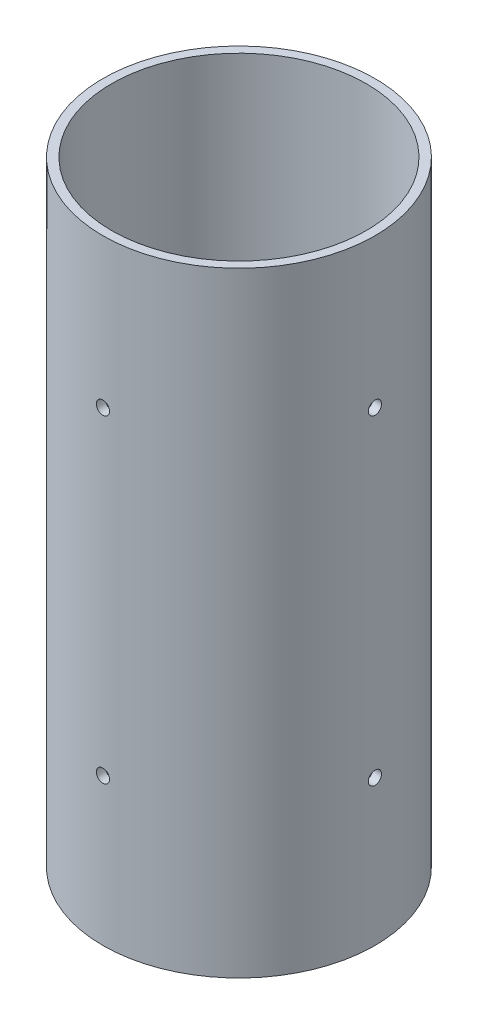
SolidWorks part; units mm, degrees
ref_plane "Front Plane" through (0, 0, 0) normal (0, 0, 1) x (1, 0, 0)
ref_plane "Top Plane" through (0, 0, 0) normal (0, 1, 0) x (1, 0, 0)
ref_plane "Right Plane" through (0, 0, 0) normal (1, 0, 0) x (0, 0, -1)
sketch "Sketch1" plane through (0, 0, 0) normal (0, 1, 0) x (1, 0, 0)
  circle A0 centre (0, 0) radius 31
  circle A1 centre (0, 0) radius 29
  dimension "D1" = 62
  dimension "D2" = 58
extrude "Boss-Extrude1" add sketch "Sketch1" along normal blind 140
sketch "Sketch2" plane through (0, 0, 0) normal (1, 0, 0) x (0, 0, -1)
  line L0 (0, 69.5884) -> (0, 34.5884) construction
  line L1 (0, 69.5884) -> (0, 104.5884) construction
  circle A0 centre (0, 33.0884) radius 1.5
  circle A1 centre (0, 106.0884) radius 1.5
  dimension "D2" = 3
  dimension "D1" = 35
extrude "Cut-Extrude1" cut sketch "Sketch2" against normal through all both and the other way through all
sketch "Sketch3" plane through (0, 0, 0) normal (0, 0, 1) x (1, 0, 0)
  line L0 (0, 70) -> (0, 35) construction
  line L2 (0, 0) -> (0, 70) construction
  line L3 (0, 70) -> (0, 104.5884) construction
  circle A0 centre (0, 106.0884) radius 1.5
  circle A1 centre (0, 33.5) radius 1.5
extrude "Cut-Extrude2" cut sketch "Sketch3" against normal through all both and the other way through all
